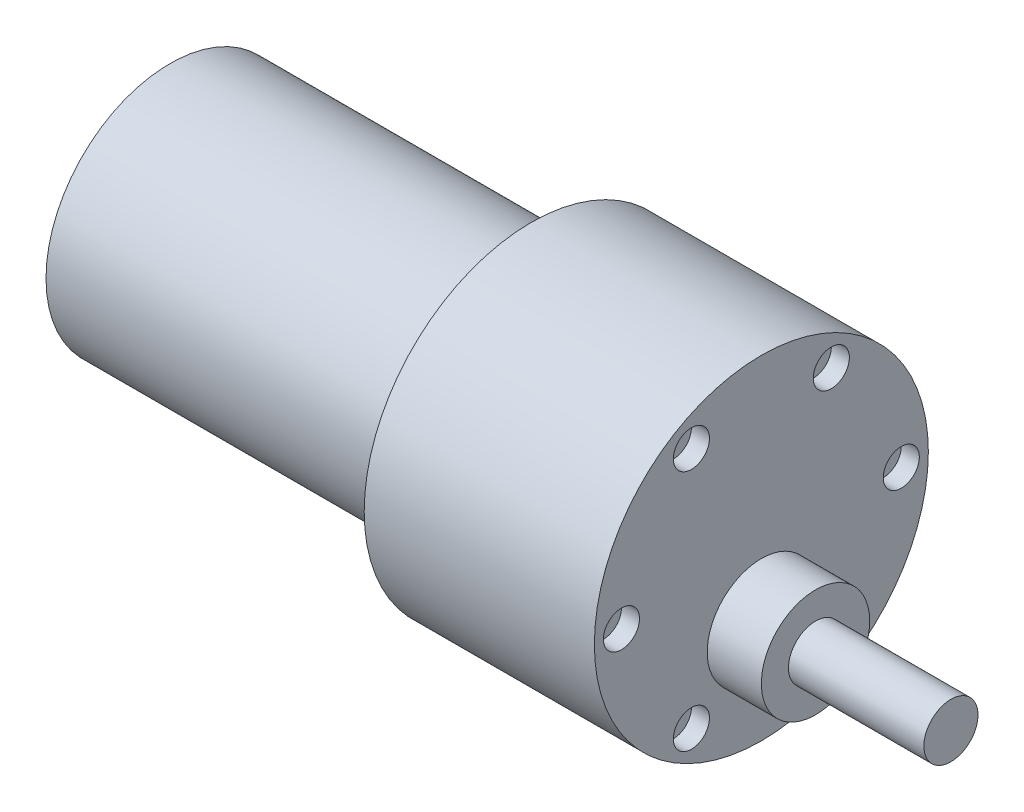
SolidWorks part; units mm, degrees
ref_plane "Front Plane" through (0, 0, 0) normal (0, 0, 1) x (1, 0, 0)
ref_plane "Top Plane" through (0, 0, 0) normal (0, 1, 0) x (1, 0, 0)
ref_plane "Right Plane" through (0, 0, 0) normal (1, 0, 0) x (0, 0, -1)
sketch "Sketch1" plane through (0, 0, 0) normal (1, 0, 0) x (0, 0, -1)
  circle A0 centre (0, 0) radius 18.5
  circle A1 centre (0, -7) radius 6 construction
  circle A2 centre (-15.5, 0) radius 2 construction
  circle A3 centre (-7.75, 13.4234) radius 2 construction
  circle A4 centre (7.75, 13.4234) radius 2 construction
  circle A5 centre (15.5, 0) radius 2 construction
  circle A6 centre (7.75, -13.4234) radius 2 construction
  circle A7 centre (-7.75, -13.4234) radius 2 construction
  point P19 (0, 0)
  dimension "D1" = 37
  dimension "D3" = 12
  dimension "D4" = 15.5
  dimension "D5" = 4
  dimension "D2" = 7
  dimension "D6" = 6
extrude "Boss-Extrude1" add sketch "Sketch1" against normal blind 25.5
sketch "Sketch2" plane through (-25.5, 0, 0) normal (-1, 0, 0) x (0, 0, 1)
  circle A0 centre (0, 0) radius 13.75
  dimension "D1" = 27.5
extrude "Boss-Extrude2" add sketch "Sketch2" along normal blind 40
sketch "Sketch3" plane through (0, 0, 0) normal (1, 0, 0) x (0, 0, -1)
  line L0 (0, 0) -> (0, -7) construction
  circle A1 centre (0, -7) radius 6
  dimension "D2" = 12
  dimension "D1" = 7
extrude "Boss-Extrude3" add sketch "Sketch3" along normal blind 6
sketch "Sketch4" plane through (6, 0, 0) normal (1, 0, 0) x (0, 0, -1)
  circle A0 centre (0, -7) radius 3
  dimension "D1" = 6
extrude "Boss-Extrude4" add sketch "Sketch4" along normal blind 15
sketch "Sketch5" plane through (0, 0, 0) normal (1, 0, 0) x (0, 0, -1)
  circle A0 centre (-15.5, 0) radius 2
  circle A1 centre (-7.75, 13.4234) radius 2
  circle A2 centre (7.75, 13.4234) radius 2
  circle A3 centre (15.5, 0) radius 2
  circle A4 centre (7.75, -13.4234) radius 2
  circle A5 centre (-7.75, -13.4234) radius 2
  point P15 (0, 0)
  dimension "D2" = 4
  dimension "D1" = 15.5
  dimension "D3" = 6
extrude "Cut-Extrude1" cut sketch "Sketch5" against normal blind 2
